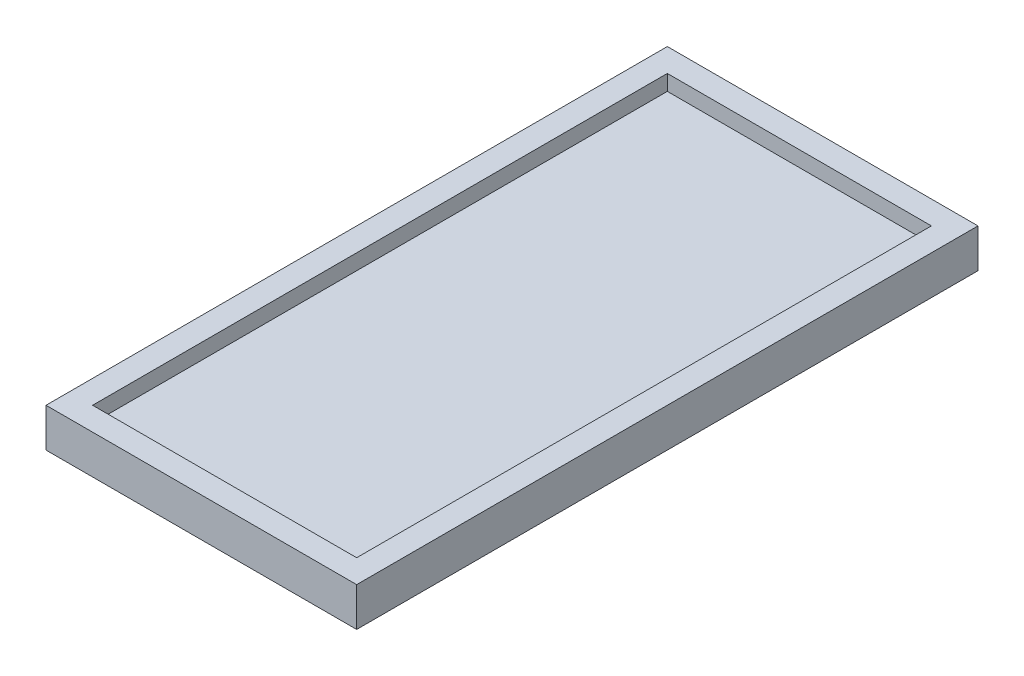
SolidWorks part; units mm, degrees
ref_plane "前视基准面" through (0, 0, 0) normal (0, 0, 1) x (1, 0, 0)
ref_plane "上视基准面" through (0, 0, 0) normal (0, 1, 0) x (1, 0, 0)
ref_plane "右视基准面" through (0, 0, 0) normal (1, 0, 0) x (0, 0, -1)
sketch "Sketch1" plane through (0, 0, 0) normal (0, 1, 0) x (1, 0, 0)
  line L1 (-20, -40) -> (20, -40)
  line L2 (-20, -40) -> (-20, 40)
  line L3 (-20, 40) -> (20, 40)
  line L4 (20, -40) -> (20, 40)
  line L5 (-20, -40) -> (20, 40) construction
  line L6 (-20, 40) -> (20, -40) construction
  point P0 (0, 0)
  dimension "D1" = 80
  dimension "D2" = 40
extrude "Boss-Extrude1" add sketch "Sketch1" along normal blind 3
sketch "Sketch2" plane through (0, 3, 0) normal (0, 1, 0) x (1, 0, 0)
  line L0 (17, 37) -> (-17, 37)
  line L1 (-17, 37) -> (-17, -37)
  line L2 (-17, -37) -> (17, -37)
  line L3 (17, -37) -> (17, 37)
  line L4 (20, -40) -> (20, 40)
  line L5 (20, 40) -> (-20, 40)
  line L6 (-20, 40) -> (-20, -40)
  line L7 (-20, -40) -> (20, -40)
  line L8 (20, -40) -> (20, 40)
  line L9 (20, 40) -> (-20, 40)
  line L10 (-20, 40) -> (-20, -40)
  line L11 (-20, -40) -> (20, -40)
  dimension "D1" = 0
  dimension "D2" = 3
extrude "Boss-Extrude2" add sketch "Sketch2" along normal blind 2
